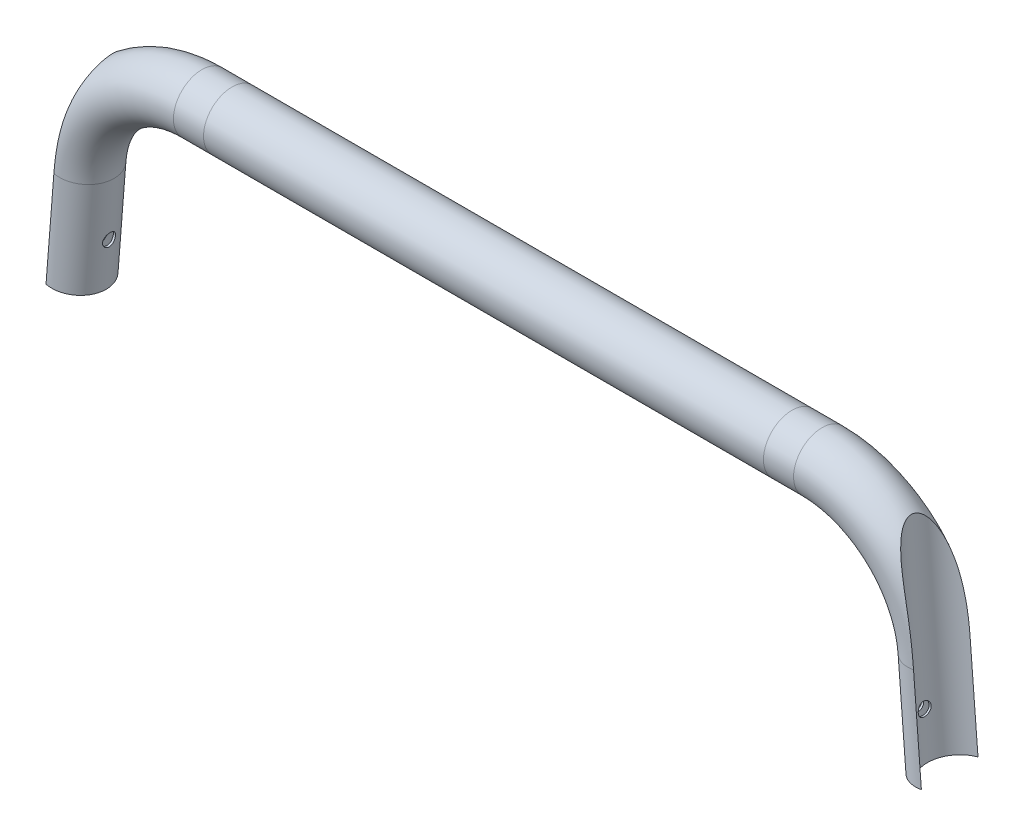
SolidWorks part; units mm, degrees
ref_plane "Front Plane" through (0, 0, 0) normal (0, 0, 1) x (1, 0, 0)
ref_plane "Top Plane" through (0, 0, 0) normal (0, 1, 0) x (1, 0, 0)
ref_plane "Right Plane" through (0, 0, 0) normal (1, 0, 0) x (0, 0, -1)
sketch "Sketch1" plane through (0, 0, 0) normal (0, 0, 1) x (1, 0, 0)
  line L0 (-108, 0) -> (108, 0)
  line L1 (0, 0) -> (0, -80) construction
  line L3 (-167.5, -80) -> (-164.4676, -41.4693)
  line L4 (-119.6063, 0) -> (-108, 0)
  line L5 (167.5, -80) -> (164.4676, -41.4693)
  line L6 (119.6063, 0) -> (108, 0)
  arc A0 (164.4676, -41.4693) -> (119.6063, 0) centre (119.6063, -45) ccw
  arc A1 (-119.6063, 0) -> (-164.4676, -41.4693) centre (-119.6063, -45) ccw
  point P4 (0, 0)
  point P11 (0, -80)
  dimension "D5" = 45
  dimension "D1" = 216
  dimension "D2" = 80
  dimension "D3" = 94.5
  dimension "D4" = 94.5
  dimension "D6" = 80
  dimension "D7" = 335
ref_plane "Plane1" through (-167.5, -80, 0) normal (-0.0785, -0.9969, 0) x (-0.9969, 0.0785, 0)
sketch "Sketch2" plane through (-167.5, -80, 0) normal (-0.0785, -0.9969, 0) x (-0.9969, 0.0785, 0)
  line L0 (-41.4693, 0) -> (0, 0) construction
  circle A0 centre (0, 0) radius 11
  circle A1 centre (0, 0) radius 10.2
  dimension "D1" = 0.8
sweep "Sweep1" add profiles "Sketch2" path "Sketch1"
sketch "Sketch3" plane through (7.2885, -92.6089, 0) normal (0.0785, -0.9969, 0) x (0.9969, 0.0785, 0)
  line L0 (160.7069, 0) -> (164.7069, 0) construction
  circle A0 centre (164.7069, 0) radius 11.2358
  dimension "D1" = 4
extrude "Cut-Extrude1" cut sketch "Sketch3" against normal through all
mirror "Mirror1" about plane through (0, 0, 0) normal (1, 0, 0) of "Cut-Extrude1"
sketch "Sketch6" plane through (7.2885, -92.6089, 0) normal (0.0785, -0.9969, 0) x (0.9969, 0.0785, 0)
  line L0 (160.7069, 0) -> (164.7069, 0) construction
  arc A0 (162.0515, 10.9175) -> (162.0515, -10.9175) centre (164.7069, 0) ccw
  arc A2 (159.7243, 10.956) -> (159.7243, -10.956) centre (164.7069, 0) ccw
  arc A3 (159.7243, -10.956) -> (162.0515, -10.9175) centre (160.7069, 0) ccw
  circle A4 centre (164.7069, 0) radius 12.0358 construction
  circle A5 centre (164.7069, 0) radius 11.2358 construction
  arc A6 (162.0515, 10.9175) -> (159.7243, 10.956) centre (160.7069, 0) ccw
  dimension "D1" = 0.8
extrude "Boss-Extrude1" add sketch "Sketch6" against normal up to next
mirror "Mirror2" about plane through (0, 0, 0) normal (1, 0, 0) of "Boss-Extrude1"
sketch "Sketch7" plane through (7.2885, -92.6089, 0) normal (0.0785, -0.9969, 0) x (0.9969, 0.0785, 0)
  line L0 (149.7069, 0) -> (160.7069, 0)
  arc A0 (162.0515, 10.9175) -> (162.0515, -10.9175) centre (160.7069, 0) ccw construction
ref_plane "Plane2" through (167.5, -80, 0) normal (0.9969, 0.0785, 0) x (0, 0, -1)
sketch "Sketch8" plane through (167.5, -80, 0) normal (0.9969, 0.0785, 0) x (0, 0, -1)
  line L0 (0, 0.0022) -> (0, 17.3022) construction
  circle A0 centre (0, 17.3022) radius 2.5
  dimension "D1" = 17.3
extrude "Cut-Extrude2" cut sketch "Sketch8" against normal up to surface (323.8568 mm away)
mirror "Mirror3" about plane through (0, 0, 0) normal (1, 0, 0) of "Cut-Extrude2"
